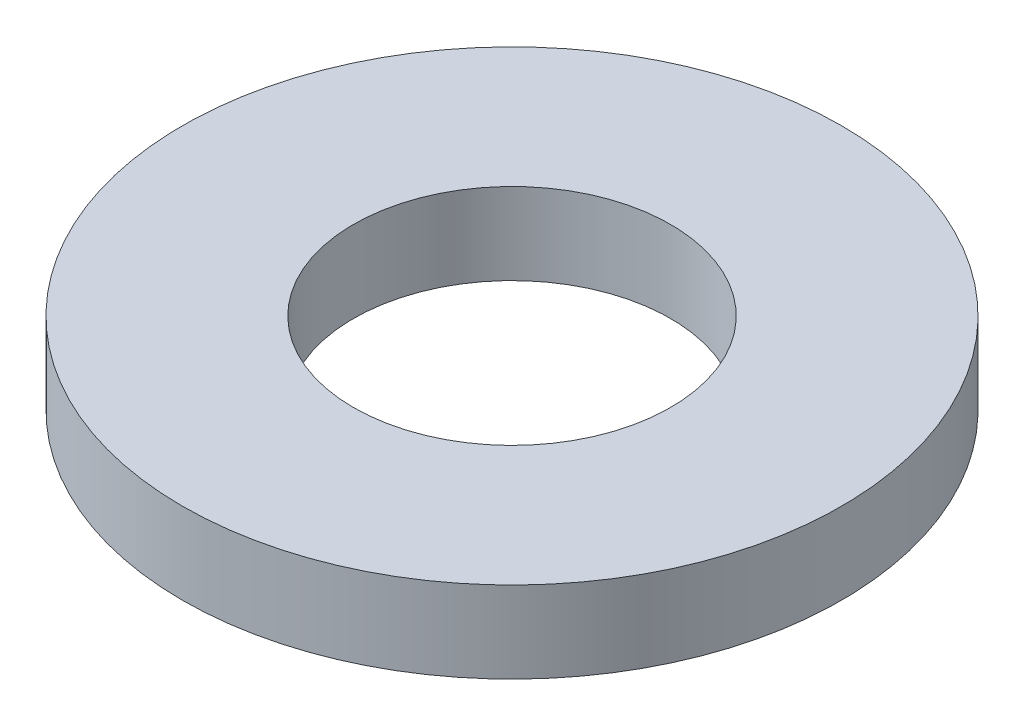
SolidWorks part; units mm, degrees
ref_plane "Front Plane" through (0, 0, 0) normal (0, 0, 1) x (1, 0, 0)
ref_plane "Top Plane" through (0, 0, 0) normal (0, 1, 0) x (1, 0, 0)
ref_plane "Right Plane" through (0, 0, 0) normal (1, 0, 0) x (0, 0, -1)
sketch "Sketch1" plane through (0, 0, 0) normal (0, 1, 0) x (1, 0, 0)
  circle A0 centre (0, 0) radius 93
  circle A1 centre (0, 0) radius 44.75
  dimension "D1" = 186
  dimension "D2" = 89.5
extrude "Boss-Extrude1" add sketch "Sketch1" along normal blind 23
